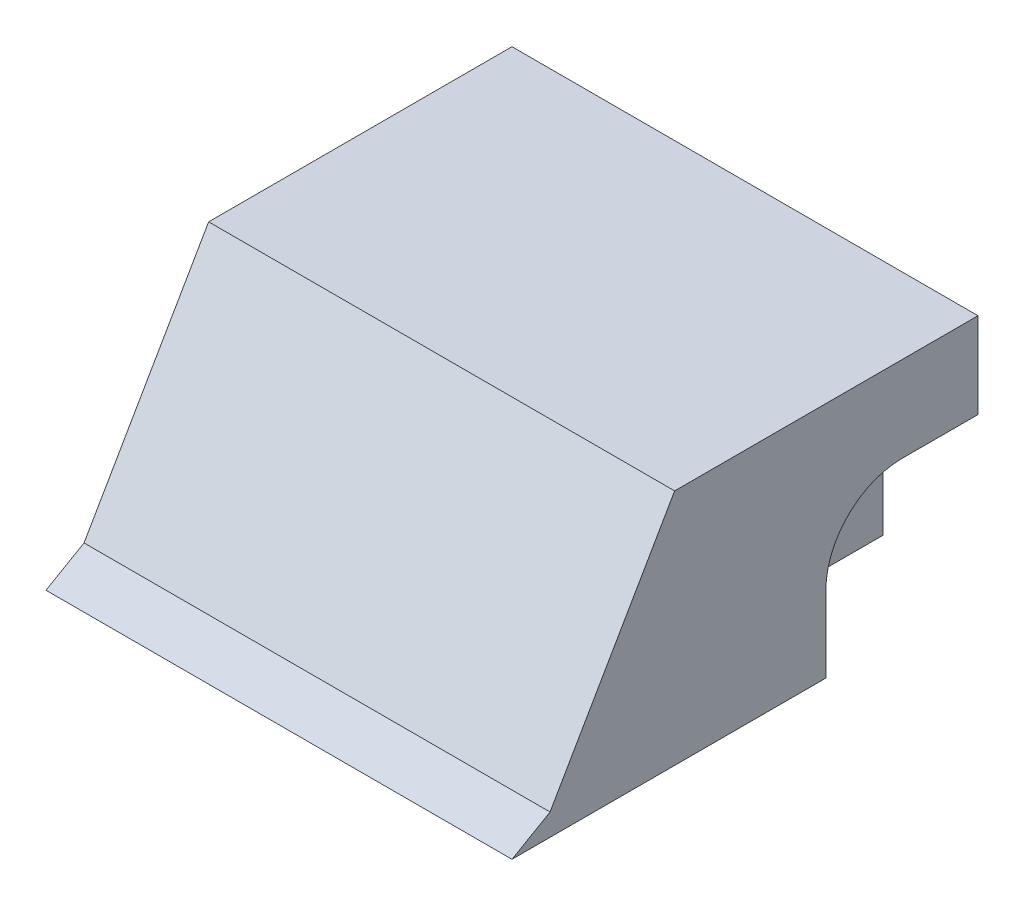
SolidWorks part; units mm, degrees
ref_plane "Plano frontal" through (0, 0, 0) normal (0, 0, 1) x (1, 0, 0)
ref_plane "Plano superior" through (0, 0, 0) normal (0, 1, 0) x (1, 0, 0)
ref_plane "Plano direito" through (0, 0, 0) normal (1, 0, 0) x (0, 0, -1)
sketch "Esboço1" plane through (0, 0, 0) normal (0, 1, 0) x (1, 0, 0)
  line L1 (49, -49) -> (-49, -49)
  line L2 (49, -49) -> (49, 49)
  line L3 (49, 49) -> (-49, 49)
  line L4 (-49, -49) -> (-49, 49)
  line L5 (49, -49) -> (-49, 49) construction
  line L6 (49, 49) -> (-49, -49) construction
  point P0 (0, 0)
  dimension "D1" = 98
  dimension "D2" = 98
extrude "Ressalto-extrusão1" add sketch "Esboço1" along normal mid plane 50
sketch "Esboço2" plane through (0, 0, 0) normal (1, 0, 0) x (0, 0, -1)
  line L0 (-49, -25) -> (37.6025, 25)
  line L1 (-49, 25) -> (49, 25) construction
  line L2 (-49, -25) -> (49, -25) construction
  line L3 (-41, -20.3812) -> (-14.7992, 25)
  line L4 (-49, 25) -> (-49, -25) construction
  line L5 (-14.7992, 25) -> (-49, 25)
  line L6 (-49, 25) -> (-49, -25)
  dimension "D1" = 30
  dimension "D2" = 60
  dimension "D3" = 8
extrude "Corte-extrusão4" cut sketch "Esboço2" against normal through all both and the other way through all contours L5 L6 L0 L3
sketch "Esboço7" plane through (0, 0, 0) normal (1, 0, 0) x (0, 0, -1)
  line L0 (-49, -25) -> (49, -25) construction
  line L2 (49, 25) -> (49, -25) construction
  line L4 (49, -9) -> (17, -9)
  line L5 (49, -9) -> (49, -25)
  line L6 (49, -25) -> (17, -25)
  line L7 (17, -9) -> (17, -25)
  line L8 (49, -25) -> (33, -25)
  line L9 (49, -25) -> (49, 7)
  line L10 (49, 7) -> (33, 7)
  line L11 (33, -25) -> (33, 7)
  circle A0 centre (33, -9) radius 16
  dimension "D1" = 32
extrude "Corte-extrusão10" cut sketch "Esboço7" against normal blind 20 from surface at 49 contours A0 | L9 L10 L11 L8 | L5 L4 L7 L6 starting at face at (49, -4.0762, 1.3598)
sketch "Esboço9" plane through (0, 0, 0) normal (1, 0, 0) x (0, 0, -1)
  line L1 (49, -25) -> (17, -25)
  line L2 (49, -25) -> (49, -9)
  line L3 (49, -9) -> (17, -9)
  line L4 (17, -25) -> (17, -9)
  line L5 (49, -25) -> (33, -25)
  line L6 (49, -25) -> (49, 7)
  line L7 (49, 7) -> (33, 7)
  line L8 (33, -25) -> (33, 7)
  circle A0 centre (33, -9) radius 16
  dimension "D1" = 32
extrude "Corte-extrusão11" cut sketch "Esboço9" along normal blind 20 from surface at -49 contours L1 L4 L3 L2 | L6 L7 L8 L5 | A0 starting at face at (-49, -4.0762, 1.3598)
